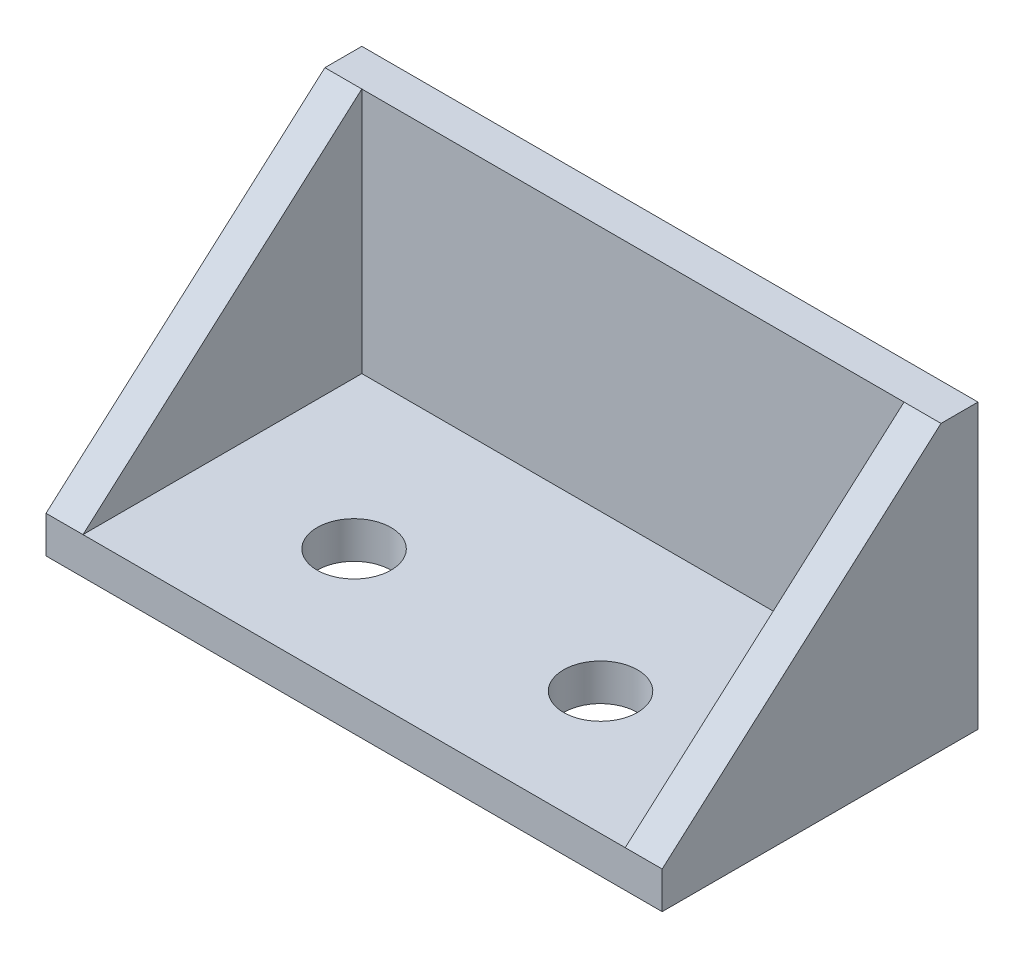
SolidWorks part; units mm, degrees
ref_plane "前基準面" through (0, 0, 0) normal (0, 0, 1) x (1, 0, 0)
ref_plane "上基準面" through (0, 0, 0) normal (0, 1, 0) x (1, 0, 0)
ref_plane "右基準面" through (0, 0, 0) normal (1, 0, 0) x (0, 0, -1)
sketch "草圖1" plane through (0, 0, 0) normal (0, 1, 0) x (1, 0, 0)
  line L0 (-26.9784, 0) -> (26.9784, 0) construction
  line L1 (-25, 5.63) -> (25, 5.63)
  line L2 (-25, 5.63) -> (-25, -20)
  line L3 (-25, -20) -> (25, -20)
  line L4 (25, 5.63) -> (25, -20)
  line L5 (0, -15.0874) -> (0, 15.0874) construction
  dimension "D1" = 5.63
  dimension "D2" = 20
  dimension "D3" = 50
  dimension "D4" = 25
extrude "填料-伸長1" add sketch "草圖1" along normal blind 3 contours L2 L3 L4 L1
sketch "草圖2" plane through (0, 3, 0) normal (0, 1, 0) x (1, 0, 0)
  line L0 (25, 5.63) -> (25, -20) construction
  line L1 (-25, 5.63) -> (25, 5.63)
  line L2 (-25, 5.63) -> (-25, 2.63)
  line L3 (-25, 2.63) -> (25, 2.63)
  line L4 (25, 5.63) -> (25, 2.63)
  dimension "D1" = 3
extrude "填料-伸長2" add sketch "草圖2" along normal blind 20
sketch "草圖6" plane through (-25, 0, 0) normal (-1, 0, 0) x (0, 0, 1)
  line L0 (-2.63, 23) -> (20, 3)
  line L1 (20, 3) -> (-2.63, 3)
  line L2 (-2.63, 3) -> (-2.63, 23)
extrude "填料-伸長3" add sketch "草圖6" against normal blind 3
mirror "鏡射1" about plane through (0, 0, 0) normal (1, 0, 0) of "填料-伸長3"
sketch "草圖7" plane through (0, 3, 0) normal (0, 1, 0) x (1, 0, 0)
  line L0 (-22, -20) -> (22, -20) construction
  line L1 (0, -12.65) -> (0, 12.65) construction
  circle A0 centre (-10, -10) radius 3
  circle A2 centre (10, -10) radius 3
  point P6 (0, 0)
  dimension "D1" = 6
  dimension "D3" = 10
  dimension "D4" = 10
extrude "除料-伸長2" cut sketch "草圖7" against normal through all
